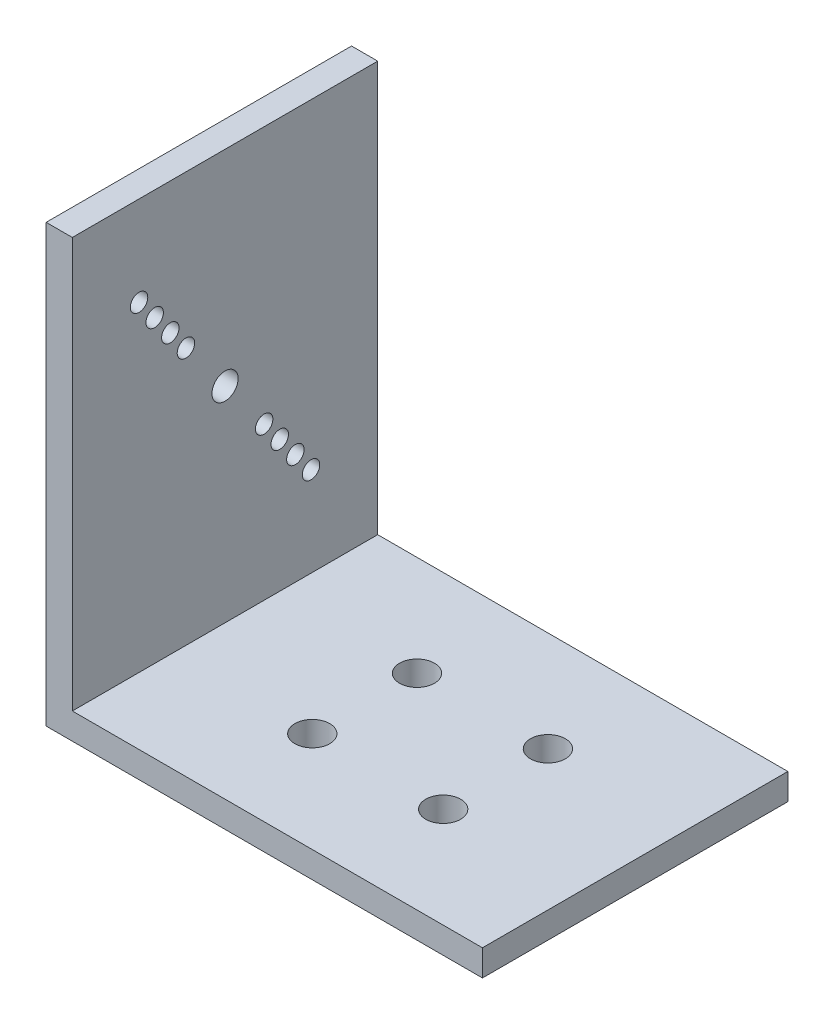
SolidWorks part; units mm, degrees
ref_plane "Front Plane" through (0, 0, 0) normal (0, 0, 1) x (1, 0, 0)
ref_plane "Top Plane" through (0, 0, 0) normal (0, 1, 0) x (1, 0, 0)
ref_plane "Right Plane" through (0, 0, 0) normal (1, 0, 0) x (0, 0, -1)
sketch "Sketch1" plane through (0, 0, 0) normal (0, 0, 1) x (1, 0, 0)
  line L0 (0, 50) -> (0, 0)
  line L1 (0, 0) -> (50, 0)
  line L2 (3, 50) -> (3, 3)
  line L3 (3, 3) -> (50, 3)
  line L4 (0, 50) -> (3, 50)
  line L5 (50, 0) -> (50, 3)
  dimension "D1" = 50
  dimension "D2" = 50
  dimension "D3" = 3
extrude "Boss-Extrude1" add sketch "Sketch1" along normal blind 35
sketch "Sketch2" plane through (0, 3, 0) normal (0, 1, 0) x (1, 0, 0)
  line L0 (3, -35) -> (50, 0) construction
  line L1 (19, -11.5) -> (34, -11.5)
  line L2 (19, -11.5) -> (19, -23.5)
  line L3 (19, -23.5) -> (34, -23.5)
  line L4 (34, -11.5) -> (34, -23.5)
  line L5 (19, -11.5) -> (34, -23.5) construction
  circle A0 centre (19, -11.5) radius 2
  circle A1 centre (34, -11.5) radius 2
  circle A2 centre (34, -23.5) radius 2
  circle A3 centre (19, -23.5) radius 2
  point P8 (26.5, -17.5)
  point P9 (26.5, -17.5)
  dimension "D3" = 4
  dimension "D1" = 12
  dimension "D2" = 15
extrude "Cut-Extrude1" cut sketch "Sketch2" against normal blind 50 contours A0 | A1 | A2 | A3
sketch "Sketch3" plane through (3, 0, 0) normal (1, 0, 0) x (0, 0, -1)
  line L0 (0, 50) -> (-35, 3) construction
  line L1 (0, 3) -> (-35, 50) construction
  circle A0 centre (-17.5, 26.5) radius 1.5
  circle A1 centre (-13.0205, 20.4847) radius 1
  circle A2 centre (-21.9795, 32.5153) radius 1
  circle A3 centre (-23.7713, 34.9215) radius 1
  circle A4 centre (-25.5631, 37.3276) radius 1
  circle A5 centre (-27.3549, 39.7337) radius 1
  circle A6 centre (-11.2287, 18.0785) radius 1
  circle A7 centre (-9.4369, 15.6724) radius 1
  circle A8 centre (-7.6451, 13.2663) radius 1
  dimension "D1" = 3
  dimension "D4" = 2
  dimension "D5" = 3
  dimension "D6" = 3
  dimension "D7" = 3
  dimension "D8" = 3
  dimension "D9" = 3
  dimension "D10" = 3
  dimension "D2" = 7.5
  dimension "D3" = 15
extrude "Cut-Extrude2" cut sketch "Sketch3" against normal blind 50
